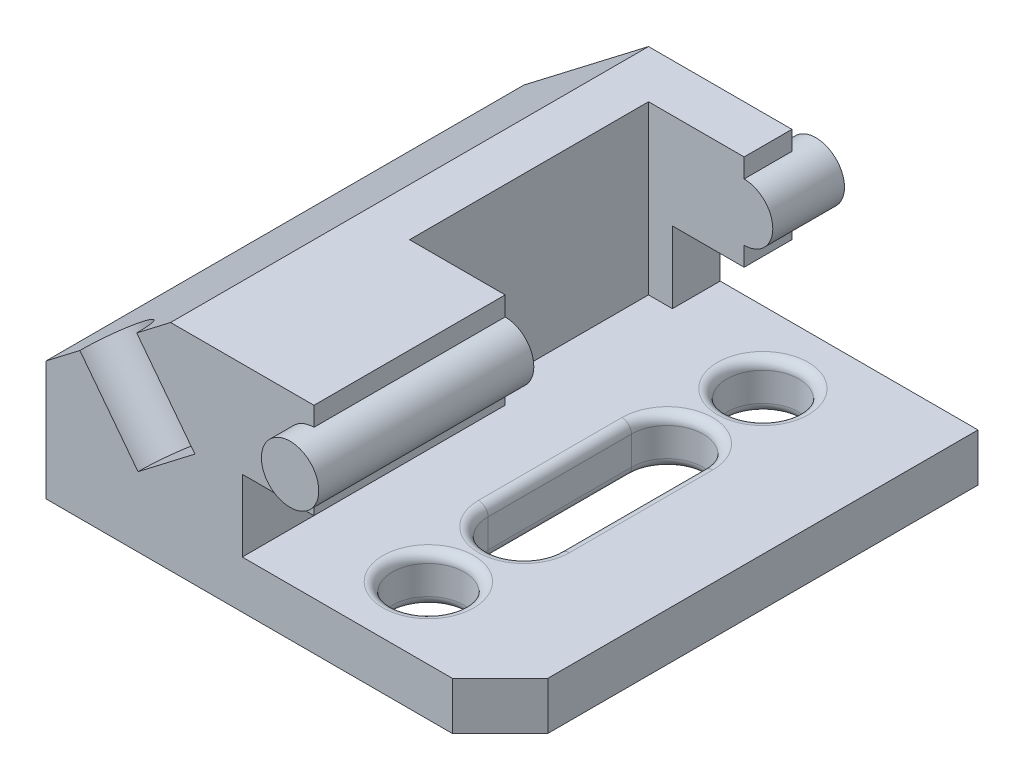
SolidWorks part; units mm, degrees
material "Alliage 1060"
ref_plane "Plan de face" through (0, 0, 0) normal (0, 0, 1) x (1, 0, 0)
ref_plane "Plan de dessus" through (0, 0, 0) normal (0, 1, 0) x (1, 0, 0)
ref_plane "Plan de droite" through (0, 0, 0) normal (1, 0, 0) x (0, 0, -1)
sketch "Esquisse1" plane through (0, 0, 0) normal (0, 0, 1) x (1, 0, 0)
  line L19 (0, 0) -> (0, 25)
  line L20 (0, 25) -> (26.0645, 45)
  line L21 (26.0645, 45) -> (56.0645, 45)
  line L22 (56.0645, 45) -> (56.0645, 25)
  line L23 (56.0645, 25) -> (41.0645, 25)
  line L24 (41.0645, 25) -> (41.0645, 10)
  line L25 (41.0645, 10) -> (95, 10)
  line L26 (95, 10) -> (95, 0)
  line L27 (95, 0) -> (0, 0)
  point P9 (44.9341, 50.6971)
  point P10 (44.9341, 23.3589)
  dimension "D1" = 95
  dimension "D2" = 30
  dimension "D3" = 20
  dimension "D4" = 15
  dimension "D5" = 15
  dimension "D6" = 10
  dimension "D7" = 25
  dimension "D8" = 52.5
extrude "Boss.-Extru.1" add sketch "Esquisse1" along normal mid plane 100
sketch "Esquisse3" plane through (0, 0, 0) normal (0, 0, 1) x (1, 0, 0)
  line L0 (56.0645, 25) -> (56.0645, 45) construction
  line L1 (56.0645, 45) -> (26.0645, 45) construction
  circle A0 centre (56.0645, 35) radius 6
  dimension "D1" = 12
  dimension "D2" = 10
extrude "Boss.-Extru.2" add sketch "Esquisse3" along normal blind 55 and the other way blind 55
sketch "Esquisse4" plane through (0, 45, 0) normal (0, 1, 0) x (1, 0, 0)
  line L0 (62.0645, -55) -> (62.0645, 55) construction
  line L1 (62.0645, 40) -> (36.0645, 40)
  line L2 (62.0645, 40) -> (62.0645, -10)
  line L3 (62.0645, -10) -> (36.0645, -10)
  line L4 (36.0645, 40) -> (36.0645, -10)
  line L5 (26.0645, -50) -> (26.0645, 50) construction
  line L6 (56.0645, 50) -> (26.0645, 50) construction
  dimension "D1" = 10
  dimension "D2" = 10
  dimension "D3" = 50
extrude "Enlèv. mat.-Extru.1" cut sketch "Esquisse4" against normal blind 35
sketch "Esquisse5" plane through (-12.0741, 15.7352, 0) normal (-0.6088, 0.7934, 0) x (0.7934, 0.6088, 0)
  line L0 (48.0726, -50) -> (15.219, -50) construction
  circle A0 centre (31.6458, -50) radius 7.5
  dimension "D1" = 15
extrude "Enlèv. mat.-Extru.2" cut sketch "Esquisse5" against normal blind 20
sketch "Esquisse8" plane through (0, 10, 0) normal (0, 1, 0) x (1, 0, 0)
  line L0 (95, -50) -> (95, 50) construction
  line L2 (95, -50) -> (41.0645, -50) construction
  line L3 (95, 50) -> (41.0645, 50) construction
  line L4 (65, 15) -> (65, -15) construction
  line L5 (72.5, 15) -> (72.5, -15)
  line L6 (57.5, 15) -> (57.5, -15)
  circle A1 centre (65, -35) radius 7.5
  circle A2 centre (65, 35) radius 7.5
  arc A3 (72.5, 15) -> (57.5, 15) centre (65, 15) ccw
  arc A4 (57.5, -15) -> (72.5, -15) centre (65, -15) ccw
  point P12 (65, 0)
  dimension "D1" = 15
  dimension "D2" = 15
  dimension "D7" = 15
  dimension "D3" = 30
  dimension "D4" = 30
  dimension "D5" = 15
  dimension "D6" = 15
  dimension "D8" = 30
  dimension "D9" = 20
extrude "Enlèv. mat.-Extru.3" cut sketch "Esquisse8" against normal through all
fillet "Congé1" radius 2 8 edges at (65, 0, -22.5) (72.5, 0, 0) (65, 0, 22.5) (65, 10, -22.5) (72.5, 10, 0) (65, 10, 22.5) (57.5, 0, 0) (57.5, 10, 0)
fillet "Congé2" radius 2 4 edges at (57.5, 10, 35) (57.5, 0, 35) (57.5, 10, -35) (57.5, 0, -35)
chamfer "Chanfrein3" distance 10 angle 45 1 edges at (95, 5, 50)
equation "\"A\" = 95mm"
equation "\"B\" = 50mm"
equation "\"C\"= 52.50"
equation "\"D1@Esquisse1\"=\"A\""
equation "\"D8@Esquisse1\"=\"C\""
equation "\"D3@Esquisse4\"=\"B\""
